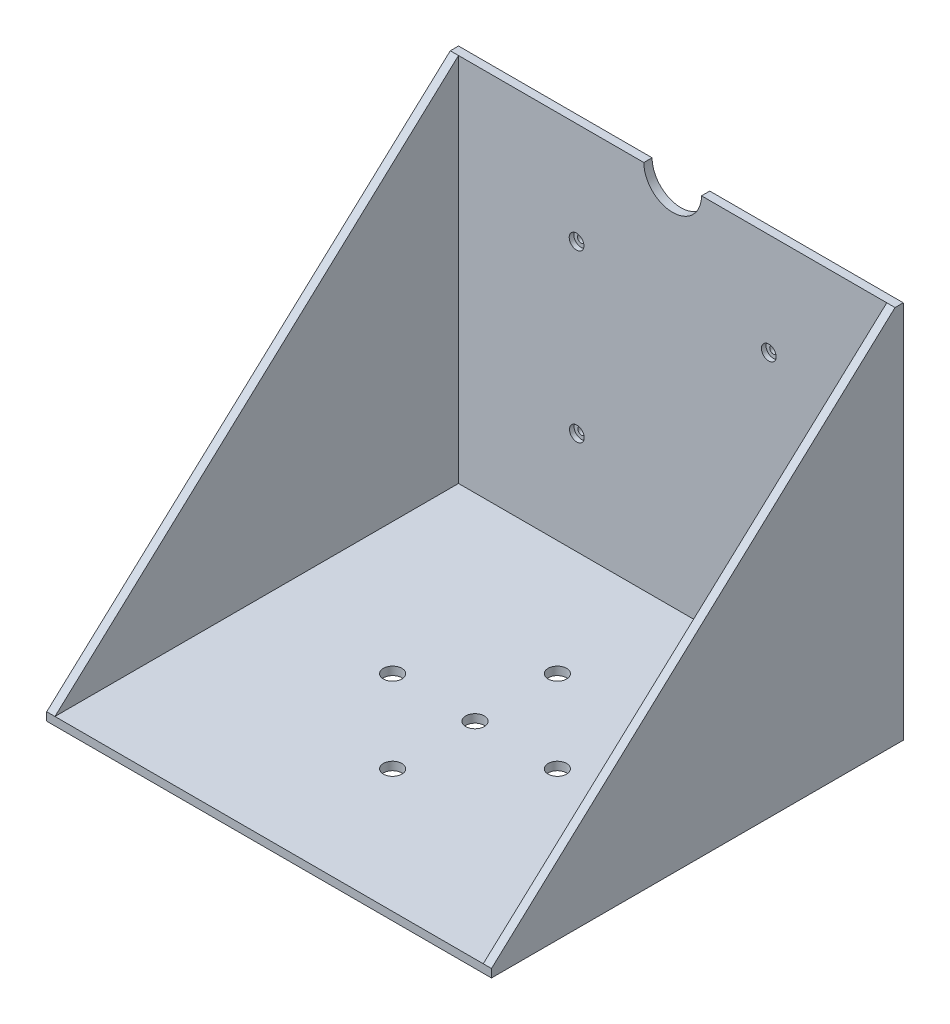
SolidWorks part; units mm, degrees
material "AISI 1020"
ref_plane "Alzado" through (0, 0, 0) normal (0, 0, 1) x (1, 0, 0)
ref_plane "Planta" through (0, 0, 0) normal (0, 1, 0) x (1, 0, 0)
ref_plane "Vista lateral" through (0, 0, 0) normal (1, 0, 0) x (0, 0, -1)
sketch "Croquis1" plane through (0, 0, 0) normal (0, 1, 0) x (1, 0, 0)
  line L1 (54, -50) -> (-54, -50)
  line L2 (54, -50) -> (54, 50)
  line L3 (54, 50) -> (-54, 50)
  line L4 (-54, -50) -> (-54, 50)
  line L5 (54, -50) -> (-54, 50) construction
  line L6 (54, 50) -> (-54, -50) construction
  point P0 (0, 0)
  dimension "D1" = 108
  dimension "D2" = 100
extrude "Saliente-Extruir2" add sketch "Croquis1" along normal blind 2
sketch "Croquis3" plane through (0, 2, 0) normal (0, 1, 0) x (1, 0, 0)
  line L0 (-54, 50) -> (-54, 48)
  line L1 (-54, 50) -> (-54, -50) construction
  line L2 (54, 50) -> (54, 48)
  line L3 (54, -50) -> (54, 50) construction
  line L4 (54, 48) -> (-54, 48)
  line L9 (-54, 50) -> (-54, -50)
  line L10 (-54, -50) -> (54, -50)
  line L11 (54, -50) -> (54, 50)
  line L12 (54, 50) -> (-54, 50)
  line L13 (-54, 50) -> (-54, -50)
  line L14 (-54, -50) -> (54, -50)
  line L15 (54, -50) -> (54, 50)
  line M6 (-54, 50) -> (-54, -50)
  line M8 (54, -50) -> (54, 50)
  line M9 (54, 50) -> (-54, 50)
  dimension "D1" = 2
  dimension "D2" = 0
extrude "Saliente-Extruir3" add sketch "Croquis3" along normal blind 90 contours L4 M8 M9 M6
sketch "Croquis4" plane through (0, 0, -48) normal (0, 0, 1) x (1, 0, 0)
  line L1 (54, 92) -> (-54, 92) construction
  line L2 (-7, 92) -> (7, 92)
  arc A0 (-7, 92) -> (7, 92) centre (0, 92) ccw
  dimension "D1" = 14
extrude "Cortar-Extruir1" cut sketch "Croquis4" against normal blind 90
sketch "Croquis5" plane through (0, 0, -48) normal (0, 0, 1) x (1, 0, 0)
  line L0 (54, 92) -> (54, 2) construction
  line L1 (-54, 92) -> (-54, 2) construction
  point P0 (-44, 79.9883)
  point P1 (44, 79.9883)
  point P2 (-44, 11.396)
  point P3 (44, 11.396)
  dimension "D1" = 10
  dimension "D2" = 10
sketch "Croquis7" plane through (0, 2, 0) normal (0, 1, 0) x (1, 0, 0)
  point P0 (0, 0)
  point P1 (20, 0)
  point P3 (-20, 0)
  point P4 (0, 20)
  point P5 (0, -20)
hole_wizard "Taladro de margen para M42" positions "Croquis13" profile "Croquis14" hole size "M4" standard "Ansi Metric"
sketch "Croquis13" plane through (0, 0, 0) normal (0, -1, 0) x (-1, 0, 0)
  point P0 (0, 20)
  point P3 (-20, 0)
  point P6 (0, -20)
  point P9 (20, 0)
  point P12 (0, 0)
sketch "Croquis14" plane through (0, 0, -20) normal (1, 0, 0) x (0, 0, -1)
  line L0 (0, 0) -> (0, 11.3519)
  line L1 (0, 11.3519) -> (2.25, 10)
  line L2 (2.25, 10) -> (2.25, 0)
  line L5 (2.25, 0) -> (0, 0)
  line L10 (0, 11.3519) -> (-2.25, 10) construction
  line L11 (0, -6.35) -> (0, 107.95) construction
  dimension "Diámetro de taladro" = 4.5
  dimension "Profundidad de taladro" = 10
  dimension "Ángulo de perforador" = 118
ref_plane "Plano1" through (54, 2, -48) normal (0, 0, -1) x (-1, 0, 0)
sketch "Croquis19" plane through (54, 0, 0) normal (1, 0, 0) x (0, 0, -1)
  line L0 (48, 92) -> (-50, 2)
  line L1 (-50, 2) -> (48, 2)
  line L3 (48, 2) -> (48, 92)
extrude "Saliente-Extruir4" add sketch "Croquis19" against normal blind 2
sketch "Croquis20" plane through (-54, 0, 0) normal (-1, 0, 0) x (0, 0, 1)
  line L0 (50, 2) -> (-48, 2)
  line L1 (-48, 57) -> (-48, -53) construction
  line L2 (-48, 2) -> (50, 2) construction
  line L3 (-48, 2) -> (-48, 92)
  line L4 (-48, 92) -> (50, 2)
extrude "Saliente-Extruir5" add sketch "Croquis20" against normal blind 2
hole_wizard "Refrentado para tornillo con cabeza troncocónica de #01" positions "Croquis26" profile "Croquis28" counterbore size "#0" standard "Ansi Inch"
sketch "Croquis26" plane through (0, 0, -48) normal (0, 0, 1) x (1, 0, 0)
  circle A1 centre (0, 47) radius 45
  point P2 (-23.3352, 67.194)
  point P4 (23.3408, 67.1987)
  point P6 (-23.2693, 26.8631)
  point P8 (23.1814, 26.9392)
  point P47 (0, 0)
  point P48 (0, 0)
  point P49 (0, 0)
  point P50 (0, 0)
  dimension "D1" = 90
sketch "Croquis28" plane through (-23.3352, 67.194, -48) normal (1, 0, 0) x (0, -1, 0)
  line L0 (0, 0) -> (0, 10.5342)
  line L1 (0, 10.5342) -> (0.889, 10)
  line L2 (0.889, 10) -> (0.889, 1.1176)
  line L3 (0.889, 1.1176) -> (1.7856, 1.1176)
  line L4 (1.7856, 1.1176) -> (1.7856, 0)
  line L5 (1.7856, 0) -> (0, 0)
  line L10 (0, 10.5342) -> (-0.889, 10) construction
  line L11 (0, -6.35) -> (0, 107.95) construction
  dimension "Diámetro de taladro" = 1.778
  dimension "Profundidad de taladro" = 10
  dimension "Diámetro de refrentado" = 3.5712
  dimension "Profundidad de refrentado" = 1.1176
  dimension "Ángulo de perforador" = 118
